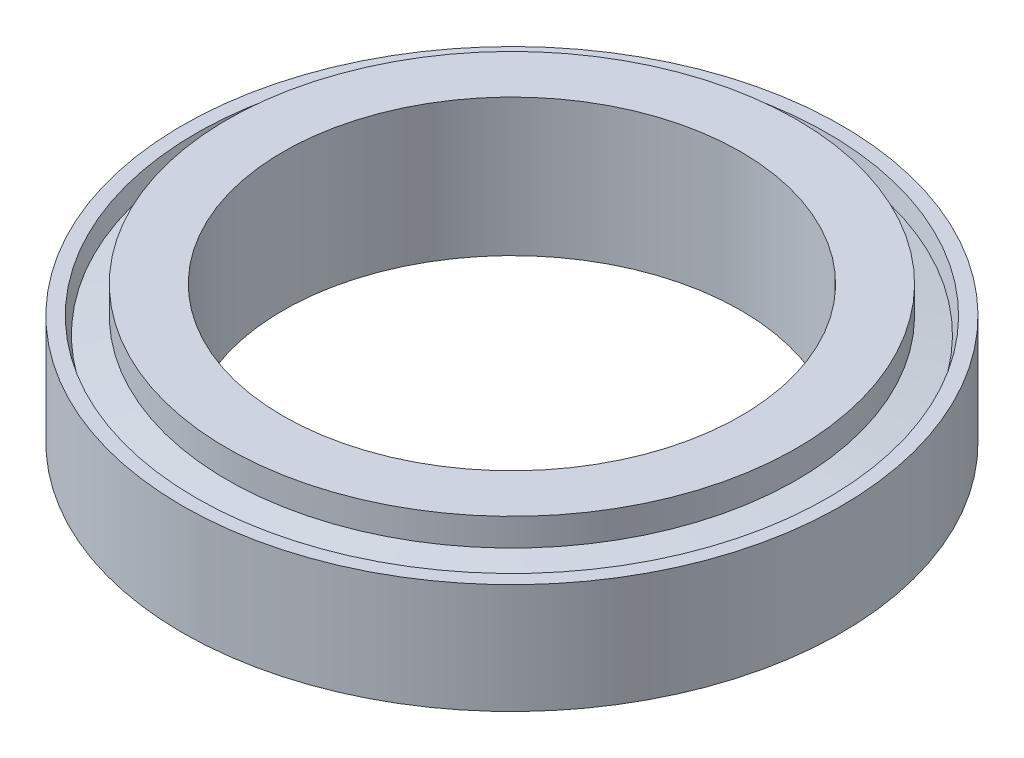
SolidWorks part; units mm, degrees
ref_plane "Ebene vorne" through (0, 0, 0) normal (0, 0, 1) x (1, 0, 0)
ref_plane "Ebene oben" through (0, 0, 0) normal (0, 1, 0) x (1, 0, 0)
ref_plane "Ebene rechts" through (0, 0, 0) normal (1, 0, 0) x (0, 0, -1)
sketch "Skizze1" plane through (0, 0, 0) normal (0, 0, 1) x (1, 0, 0)
  line L0 (0, 0) -> (0, -47104.1661) construction
  line L1 (0, 0) -> (47104.1661, 0) construction
  line L2 (32, 0) -> (36, 0)
  line L3 (36, 0) -> (36, 12)
  line L4 (36, 12) -> (34.5, 12)
  line L5 (34.5, 12) -> (32, 0)
  dimension "D1" = 72
  dimension "D2" = 12
  dimension "D3" = 64
  dimension "D4" = 69
revolve "Rotation1" add sketch "Skizze1" angle 360 about L0
sketch "Skizze4" plane through (0, 0, 0) normal (0, 0, 1) x (1, 0, 0)
  line L0 (0, 0) -> (0, 29.1548) construction
  line L1 (0, 0) -> (50000, 0) construction
  line L3 (26.5, 0) -> (25, 0)
  line L4 (25, 0) -> (25, 15)
  line L5 (25, 15) -> (31.1, 15)
  line L6 (31.1, 15) -> (31.1, 12)
  line L7 (31.1, 12) -> (28.6, 12)
  line L8 (28.6, 12) -> (26.5, 0)
  line L9 (-32, 0) -> (32, 0) construction
  dimension "D1" = 15
  dimension "D2" = 50
  dimension "D3" = 62.2
  dimension "D4" = 3
  dimension "D5" = 2.5
  dimension "D6" = 53
revolve "Rotation2" add sketch "Skizze4" angle 360 about L0
sketch "Skizze5" plane through (0, 0, 0) normal (0, 0, 1) x (1, 0, 0)
  line L0 (32.0418, 0.3771) -> (26.7457, 1.3085)
  line L1 (26.7457, 1.3085) -> (28.4772, 11.1541)
  line L2 (28.4772, 11.1541) -> (34.0278, 10.1779)
  line L3 (34.0278, 10.1779) -> (32.0418, 0.3771)
  line L4 (0, 0) -> (0, -50000) construction
revolve "Rotation3" add sketch "Skizze5" angle 360 about L4
